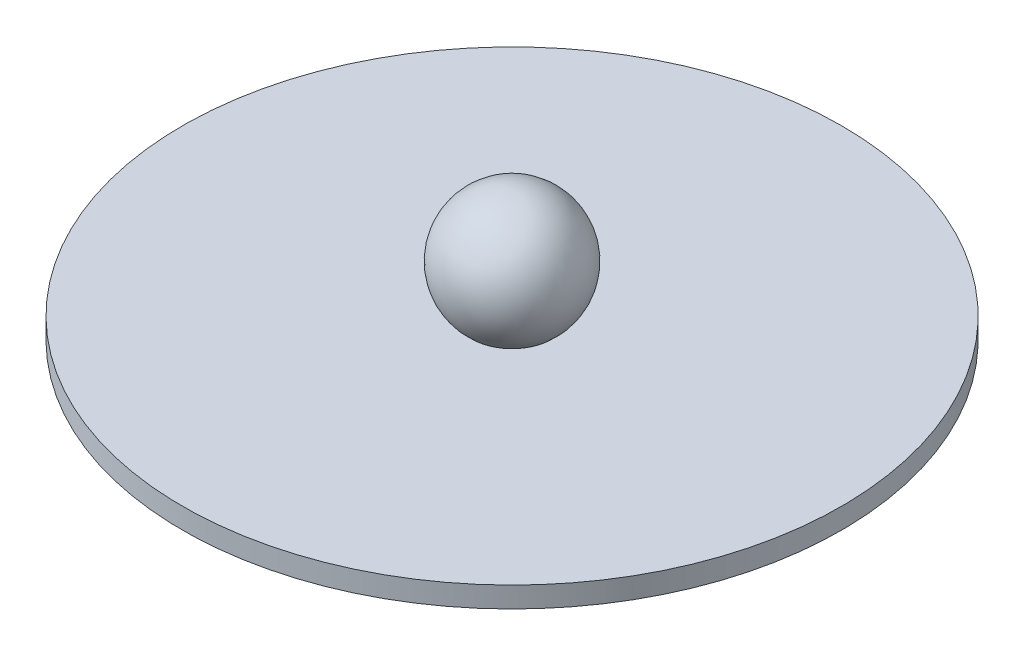
SolidWorks part; units mm, degrees
ref_plane "Front" through (0, 0, 0) normal (0, 0, 1) x (1, 0, 0)
ref_plane "Top" through (0, 0, 0) normal (0, 1, 0) x (1, 0, 0)
ref_plane "Right" through (0, 0, 0) normal (1, 0, 0) x (0, 0, -1)
sketch "Sketch1" plane through (0, 0, 0) normal (0, 0, 1) x (1, 0, 0)
  line L0 (0, 0) -> (0, 90.5826) construction
  line L1 (100.965, 12.7) -> (100.965, 6.35)
  line L2 (100.965, 6.35) -> (95.885, 6.35)
  line L3 (95.885, 6.35) -> (89.535, 0)
  line L4 (89.535, 0) -> (0, 0)
  line L5 (0, 0) -> (0, 12.7)
  line L6 (0, 12.7) -> (100.965, 12.7)
  dimension "D1" = 100.965
  dimension "D2" = 12.7
  dimension "D3" = 45
  dimension "D4" = 6.35
  dimension "D5" = 5.08
revolve "Revolve1" add sketch "Sketch1" angle 360 about L0
sketch "Sketch2" plane through (0, 0, 0) normal (0, 0, 1) x (1, 0, 0)
  line L0 (0, 0) -> (0, 27.2643) construction
  line L1 (0, 46.3143) -> (0, 8.2143)
  arc A0 (0, 8.2143) -> (0, 46.3143) centre (0, 27.2643) ccw
  dimension "D1" = 38.1
revolve "Revolve2" add sketch "Sketch2" angle 360 about L0
